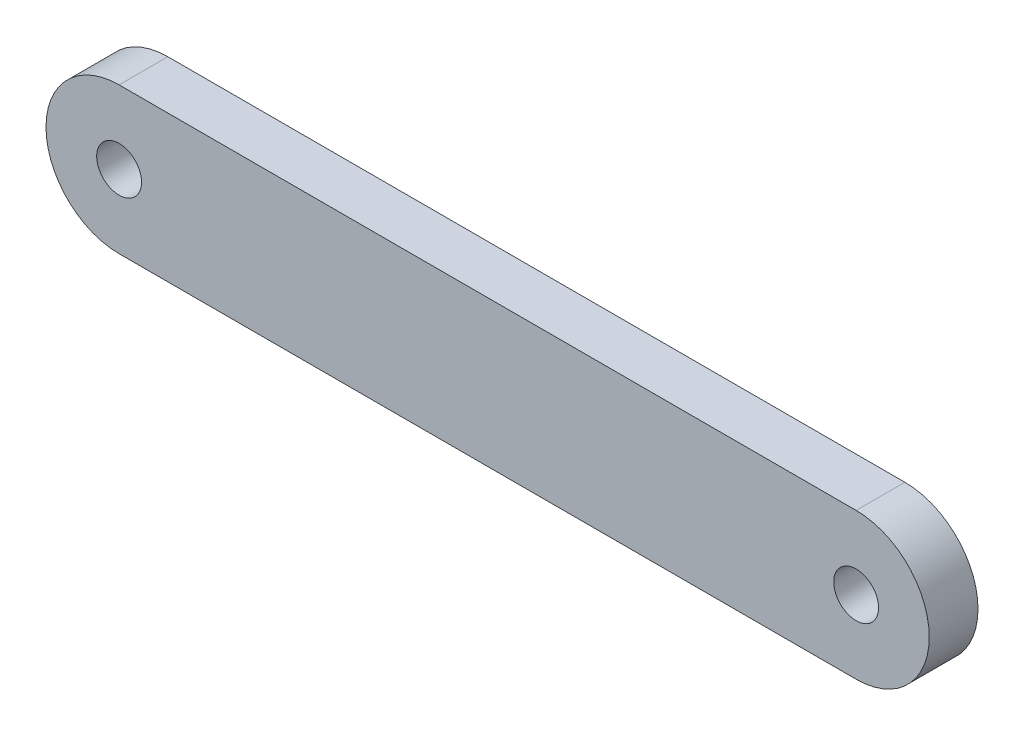
SolidWorks part; units mm, degrees
ref_plane "前视基准面" through (0, 0, 0) normal (0, 0, 1) x (1, 0, 0)
ref_plane "上视基准面" through (0, 0, 0) normal (0, 1, 0) x (1, 0, 0)
ref_plane "右视基准面" through (0, 0, 0) normal (1, 0, 0) x (0, 0, -1)
other "Configuration Table"
sketch "草图1" plane through (0, 0, 0) normal (0, 0, 1) x (1, 0, 0)
  line L1 (-37.8, 7.5) -> (37.8, 7.5)
  line L3 (-37.8, -7.5) -> (37.8, -7.5)
  line L5 (-37.8, 7.5) -> (37.8, -7.5) construction
  line L6 (-37.8, -7.5) -> (37.8, 7.5) construction
  arc A0 (-37.8, 7.5) -> (-37.8, -7.5) centre (-37.8, 0) ccw
  arc A1 (37.8, 7.5) -> (37.8, -7.5) centre (37.8, 0) cw
  circle A2 centre (-37.8, 0) radius 2.3
  circle A3 centre (37.8, 0) radius 2.3
  point P0 (0, 0)
  point P11 (0, 0)
  point P12 (0, 0)
  dimension "D1" = 4.6
  dimension "D2" = 4.6
  dimension "D3" = 75.6
  dimension "D4" = 15
extrude "凸台-拉伸1" add sketch "草图1" along normal blind 5
equation "\"fi\"=4.6"
equation "\"D1@草图1\"=\"fi\""
equation "\"D2@草图1\"=\"fi\""
equation "\"b0\"=75.6"
equation "\"D3@草图1\"=\"b0\""
equation "\"width\"=15"
equation "\"D4@草图1\"=\"width\""
equation "\"depth\"=5"
equation "\"D1@凸台-拉伸1\"=\"depth\""
